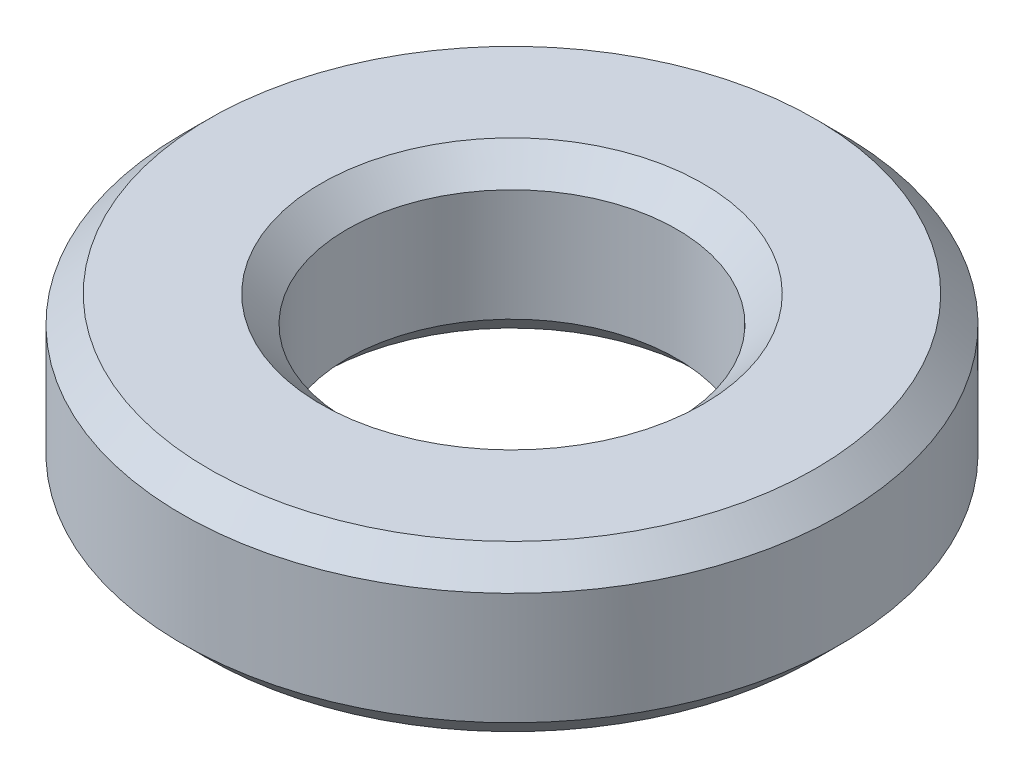
SolidWorks part; units mm, degrees
ref_plane "Front" through (0, 0, 0) normal (0, 0, 1) x (1, 0, 0)
ref_plane "Top" through (0, 0, 0) normal (0, 1, 0) x (1, 0, 0)
ref_plane "Right" through (0, 0, 0) normal (1, 0, 0) x (0, 0, -1)
sketch "Sketch1" plane through (0, 0, 0) normal (0, 0, 1) x (1, 0, 0)
  line L0 (0, 1.6446) -> (0, -1.6446) construction
  line L2 (3.175, 0.7937) -> (3.175, -0.7937)
  line L5 (3.175, 0.7937) -> (1.5875, 0.7938)
  line L6 (1.5875, 0.7938) -> (1.5875, -0.7937)
  line L7 (1.5875, -0.7937) -> (3.175, -0.7937)
  point P7 (1.5875, 0)
  dimension "D1" = 1.5875
  dimension "D2" = 3.175
  dimension "D3" = 6.35
revolve "Revolve1" add sketch "Sketch1" angle 360 about L0
chamfer "Chamfer1" distance 0.254 angle 45 4 edges at (-3.175, -0.7938, 0) (-3.175, 0.7937, 0) (-1.5875, 0.7937, 0) (-1.5875, -0.7938, 0)
